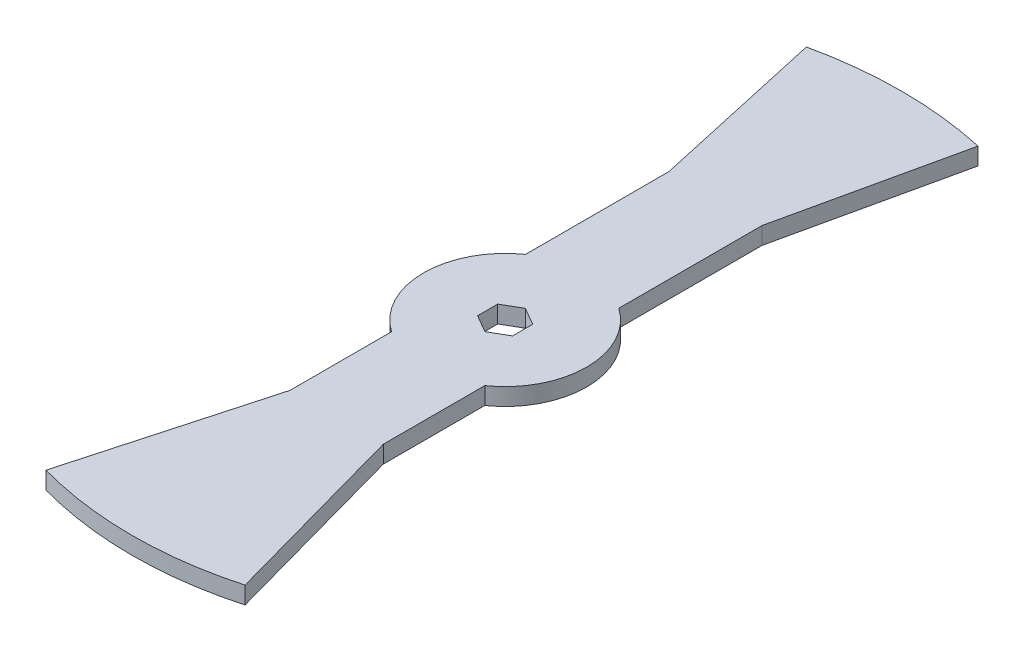
SolidWorks part; units mm, degrees
material "Cast Alloy Steel"
ref_plane "Front Plane" through (0, 0, 0) normal (0, 0, 1) x (1, 0, 0)
ref_plane "Top Plane" through (0, 0, 0) normal (0, 1, 0) x (1, 0, 0)
ref_plane "Right Plane" through (0, 0, 0) normal (1, 0, 0) x (0, 0, -1)
sketch "Sketch1" plane through (0, 0, 0) normal (0, 1, 0) x (1, 0, 0)
  line L0 (0, 107.95) -> (0, -107.95) construction
  line L1 (-2.7488, 12.399) -> (-23.3647, 105.3912) construction
  line L2 (-3.3875, -12.2399) -> (-27.0998, -97.9192) construction
  line L3 (3.3875, -12.2399) -> (27.0998, -97.9192) construction
  line L4 (2.7488, 12.399) -> (23.3647, 105.3912) construction
  line L5 (-12.7, 57.286) -> (-12.7, -45.8886)
  line L6 (12.7, 57.286) -> (12.7, -45.8886)
  line L7 (-23.3647, 105.3912) -> (-12.7, 57.286)
  line L8 (12.7, 57.286) -> (23.3647, 105.3912)
  line L9 (-12.7, -45.8886) -> (-27.0998, -97.9192)
  line L10 (12.7, -45.8886) -> (27.0998, -97.9192)
  circle A0 centre (0, 0) radius 12.7 construction
  circle A1 centre (0, 0) radius 107.95 construction
  circle A2 centre (0, 0) radius 101.6 construction
  arc A3 (-27.0998, -97.9192) -> (27.0998, -97.9192) centre (0, 0) ccw
  arc A4 (-23.3647, 105.3912) -> (23.3647, 105.3912) centre (0, 0) cw
  dimension "D1" = 25.4
  dimension "D2" = 25
  dimension "D3" = 215.9
  dimension "D4" = 203.2
  dimension "D5" = 30.94
extrude "Boss-Extrude1" add sketch "Sketch1" along normal mid plane 4.699
sketch "Sketch2" plane through (0, 2.3495, 0) normal (0, 1, 0) x (1, 0, 0)
  line L1 (4.7625, -2.7496) -> (4.7625, 2.7496)
  line L2 (4.7625, 2.7496) -> (0, 5.4993)
  line L3 (0, 5.4993) -> (-4.7625, 2.7496)
  line L4 (-4.7625, 2.7496) -> (-4.7625, -2.7496)
  line L5 (-4.7625, -2.7496) -> (0, -5.4993)
  line L6 (0, -5.4993) -> (4.7625, -2.7496)
  circle A0 centre (0, 0) radius 4.7625 construction
  dimension "D1" = 9.525
extrude "Cut-Extrude1" cut sketch "Sketch2" against normal up to next
sketch "Sketch3" plane through (0, -2.3495, 0) normal (0, -1, 0) x (1, 0, 0)
  line L0 (4.7625, -2.7496) -> (0, -5.4993) construction
  line L1 (0, -5.4993) -> (-4.7625, -2.7496) construction
  line L2 (4.7625, 2.7496) -> (4.7625, -2.7496) construction
  line L3 (-4.7625, -2.7496) -> (-4.7625, 2.7496) construction
  line L4 (-4.7625, 2.7496) -> (0, 5.4993) construction
  line L5 (0, 5.4993) -> (4.7625, 2.7496) construction
  line L6 (4.7625, -2.7496) -> (0, -5.4993)
  line L7 (0, -5.4993) -> (-4.7625, -2.7496)
  line L8 (4.7625, 2.7496) -> (4.7625, -2.7496)
  line L9 (-4.7625, -2.7496) -> (-4.7625, 2.7496)
  line L10 (-4.7625, 2.7496) -> (0, 5.4993)
  line L11 (0, 5.4993) -> (4.7625, 2.7496)
  circle A0 centre (0, 0) radius 22.225
  dimension "D1" = 44.45
extrude "Boss-Extrude2" add sketch "Sketch3" against normal up to surface (4.699 mm away) up to face at (0, 2.3495, 0)
